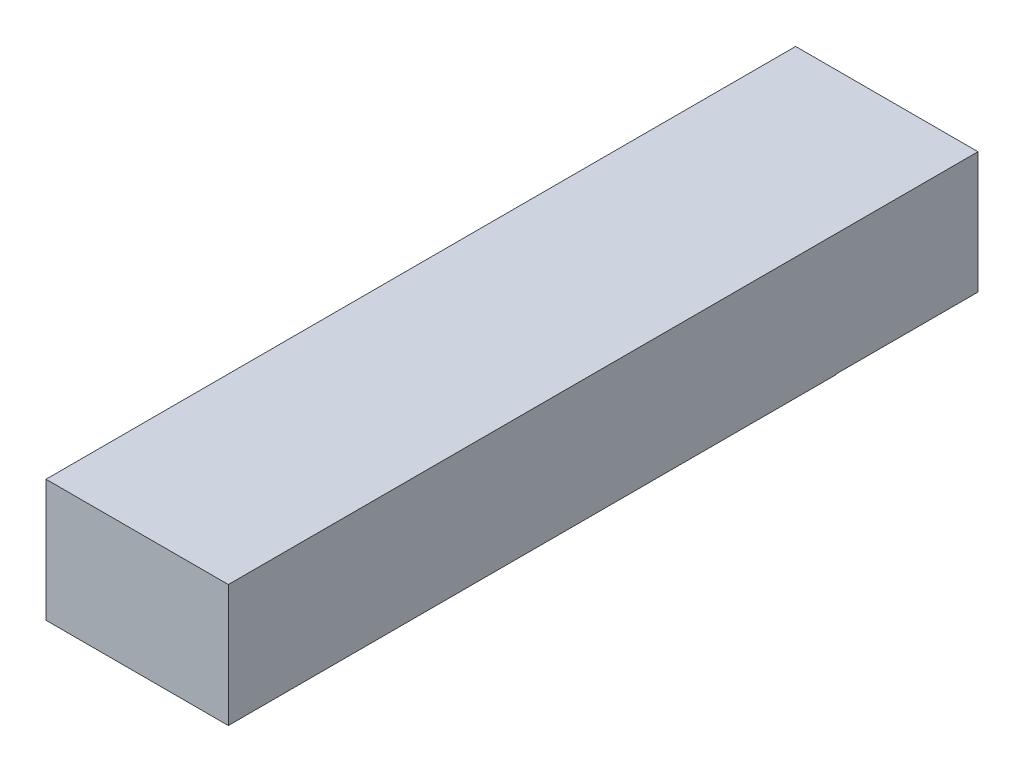
SolidWorks part; units mm, degrees
ref_plane "Front Plane" through (0, 0, 0) normal (0, 0, 1) x (1, 0, 0)
ref_plane "Top Plane" through (0, 0, 0) normal (0, 1, 0) x (1, 0, 0)
ref_plane "Right Plane" through (0, 0, 0) normal (1, 0, 0) x (0, 0, -1)
sketch "Sketch3" plane through (0, 0, 0) normal (0, 0, 1) x (1, 0, 0)
  line L0 (0, 0) -> (0, 2) construction
  line L1 (0, 0) -> (0, -2) construction
  line L2 (0, -2) -> (-1, -2) construction
  line L3 (-1, -2) -> (-1, 0) construction
  line L4 (-1, 0) -> (-2.5, 0) construction
  line L5 (-2.5, 0) -> (-2.5, 2) construction
  line L6 (-2.5, 2) -> (0, 2) construction
  line L7 (-1.2, -2) -> (-4.5, -2)
  line L8 (-4.5, -2) -> (-4.5, 4)
  line L9 (-4.5, 4) -> (4.5, 4)
  line L11 (2.8, 2) -> (-2.8, 2)
  line L12 (-2.8, 2) -> (-2.8, -0.3)
  line L13 (-2.8, -0.3) -> (-1.2, -0.3)
  line L14 (-1.2, -0.3) -> (-1.2, -2)
  line L15 (1.2, -0.3) -> (1.2, -2)
  line L16 (2.8, -0.3) -> (1.2, -0.3)
  line L17 (2.8, 2) -> (2.8, -0.3)
  line L18 (4.5, -2) -> (4.5, 4)
  line L19 (1.2, -2) -> (4.5, -2)
  dimension "D1" = 2
  dimension "D2" = 2
  dimension "D3" = 1
  dimension "D4" = 1.5
  dimension "D5" = 2.5
  dimension "D6" = 3.5
  dimension "D7" = 2
  dimension "D8" = 6
  dimension "D9" = 2.8
  dimension "D10" = 2.3
  dimension "D11" = 1.6
  dimension "D12" = 0.2
extrude "Boss-Extrude1" add sketch "Sketch3" along normal blind 7
sketch "Sketch4" plane through (0, 0, 7) normal (0, 0, 1) x (1, 0, 0)
  line L0 (-4.5, 4) -> (4.5, 4)
  line L1 (-4.5, 4) -> (-4.5, -2.0287)
  line L2 (4.5, 4) -> (4.5, -2.0287)
  line L3 (-4.5, -2.0287) -> (4.5, -2.0287)
  dimension "D1" = 9
  dimension "D2" = 6.0287
extrude "Boss-Extrude2" add sketch "Sketch4" along normal blind 30
